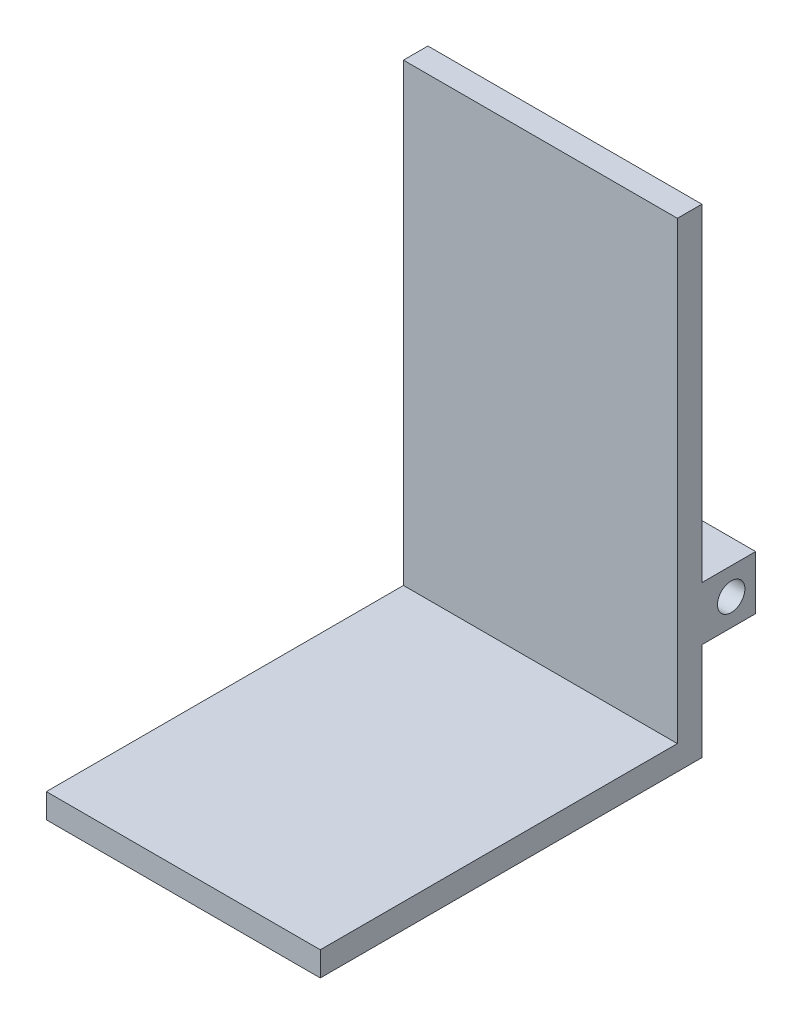
SolidWorks part; units mm, degrees
ref_plane "Front Plane" through (0, 0, 0) normal (0, 0, 1) x (1, 0, 0)
ref_plane "Top Plane" through (0, 0, 0) normal (0, 1, 0) x (1, 0, 0)
ref_plane "Right Plane" through (0, 0, 0) normal (1, 0, 0) x (0, 0, -1)
sketch "Sketch1" plane through (0, 0, 0) normal (0, 1, 0) x (1, 0, 0)
  line L1 (-14, -19.5) -> (14, -19.5)
  line L2 (-14, -19.5) -> (-14, 19.5)
  line L3 (-14, 19.5) -> (14, 19.5)
  line L4 (14, -19.5) -> (14, 19.5)
  line L5 (-14, -19.5) -> (14, 19.5) construction
  line L6 (-14, 19.5) -> (14, -19.5) construction
  point P0 (0, 0)
  dimension "D1" = 39
  dimension "D2" = 28
extrude "Boss-Extrude1" add sketch "Sketch1" along normal blind 2.5
sketch "Sketch2" plane through (0, 2.5, 0) normal (0, 1, 0) x (1, 0, 0)
  line L0 (14, -19.5) -> (14, 19.5) construction
  line L1 (-14, 19.5) -> (14, 19.5)
  line L2 (-14, 19.5) -> (-14, 17)
  line L3 (-14, 17) -> (14, 17)
  line L4 (14, 19.5) -> (14, 17)
  dimension "D1" = 2.5
extrude "Boss-Extrude2" add sketch "Sketch2" along normal blind 46.5
sketch "Sketch3" plane through (14, 0, 0) normal (1, 0, 0) x (0, 0, -1)
  line L0 (19.5, 49) -> (19.5, 0) construction
  line L1 (19.5, 15.5) -> (25, 15.5)
  line L2 (19.5, 15.5) -> (19.5, 10)
  line L3 (19.5, 10) -> (25, 10)
  line L4 (25, 15.5) -> (25, 10)
  line L5 (-19.5, 0) -> (19.5, 0) construction
  circle A0 centre (22.5, 12.75) radius 1.4
  dimension "D3" = 2.8
  dimension "D1" = 5.5
  dimension "D2" = 5.5
  dimension "D4" = 10
  dimension "D5" = 2.75
  dimension "D6" = 2.5
extrude "Boss-Extrude3" add sketch "Sketch3" against normal up to surface (28 mm away) up to face at (-14, 21.0417, -8.7083)
